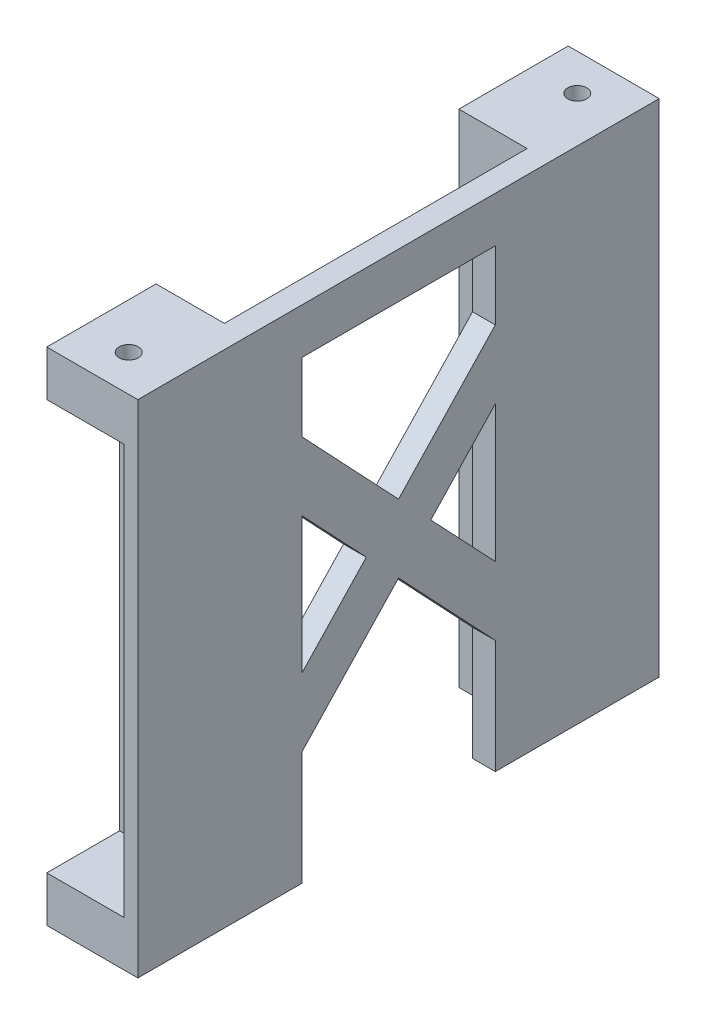
SolidWorks part; units mm, degrees
ref_plane "Спереди" through (0, 0, 0) normal (0, 0, 1) x (1, 0, 0)
ref_plane "Сверху" through (0, 0, 0) normal (0, 1, 0) x (1, 0, 0)
ref_plane "Справа" through (0, 0, 0) normal (1, 0, 0) x (0, 0, -1)
ref_plane "Плоскость4" through (0, 139.196, 0) normal (0, 1, 0) x (1, 0, 0)
sketch "Эскиз1" plane through (0, 139.196, 0) normal (0, 1, 0) x (1, 0, 0)
  line L9 (108.059, -32.2731) -> (128.059, -32.2731)
  line L10 (108.059, -32.2731) -> (128.059, -32.2731) construction
  line L11 (108.059, -32.2731) -> (108.059, -56.2731)
  line L14 (108.059, -56.2731) -> (123.059, -56.2731)
  line L15 (123.059, -56.2731) -> (123.059, -68.2731)
  line L16 (123.059, -68.2731) -> (128.059, -68.2731)
  line L17 (128.059, -34.1) -> (128.059, 34.1) construction
  line L18 (128.059, -68.2731) -> (128.059, -32.2731)
  circle A1 centre (120.059, -40.2731) radius 2.1
extrude "Бобышка-Вытянуть1" add sketch "Эскиз1" along normal blind 10
ref_plane "Плоскость5" through (0, 149.196, 0) normal (0, 1, 0) x (1, 0, 0)
sketch "Эскиз2" plane through (0, 149.196, 0) normal (0, 1, 0) x (1, 0, 0)
  line L9 (128.059, -32.2731) -> (125.059, -32.2731)
  line L10 (128.059, -32.2731) -> (108.059, -32.2731) construction
  line L11 (125.059, -32.2731) -> (125.059, -48.2731)
  line L12 (125.059, -48.2731) -> (108.059, -48.2731)
  line L13 (108.059, -48.2731) -> (21.559, -48.2731) construction
  line L14 (108.059, -32.2731) -> (108.059, -56.2731) construction
  line L15 (108.059, -48.2731) -> (108.059, -56.2731)
  line L16 (108.059, -56.2731) -> (123.059, -56.2731)
  line L17 (123.059, -56.2731) -> (123.059, -68.2731)
  line L18 (123.059, -68.2731) -> (128.059, -68.2731)
  line L19 (128.059, -68.2731) -> (128.059, -32.2731)
extrude "Бобышка-Вытянуть2" add sketch "Эскиз2" along normal blind 90
sketch "Эскиз3" plane through (0, 139.196, 0) normal (0, 1, 0) x (1, 0, 0)
  line L0 (123.059, -110.7731) -> (123.059, -122.7731)
  line L1 (123.059, -122.7731) -> (108.059, -122.7731)
  line L2 (108.059, -122.7731) -> (108.059, -146.7731)
  line L3 (108.059, -146.7731) -> (128.059, -146.7731)
  line L4 (128.059, -34.1) -> (128.059, 34.1) construction
  line L5 (128.059, -146.7731) -> (128.059, -110.7731)
  line L6 (128.059, -110.7731) -> (123.059, -110.7731)
  circle A0 centre (120.059, -138.7731) radius 2.1
extrude "Бобышка-Вытянуть3" add sketch "Эскиз3" along normal blind 10 separate body
sketch "Эскиз4" plane through (0, 149.196, 0) normal (0, 1, 0) x (1, 0, 0)
  line L0 (123.059, -110.7731) -> (123.059, -122.7731)
  line L1 (123.059, -122.7731) -> (108.059, -122.7731)
  line L2 (108.059, -122.7731) -> (108.059, -130.7731)
  line L3 (108.059, -130.7731) -> (125.059, -130.7731)
  line L4 (-8.25, -130.7731) -> (8.25, -130.7731) construction
  line L5 (125.059, -130.7731) -> (125.059, -146.7731)
  line L6 (108.059, -146.7731) -> (128.059, -146.7731) construction
  line L7 (125.059, -146.7731) -> (128.059, -146.7731)
  line L8 (128.059, -146.7731) -> (128.059, -110.7731)
  line L9 (128.059, -110.7731) -> (123.059, -110.7731)
extrude "Бобышка-Вытянуть4" add sketch "Эскиз4" along normal blind 90
ref_plane "Плоскость6" through (128.059, 0, 0) normal (1, 0, 0) x (0, 0, -1)
sketch "Эскиз5" plane through (128.059, 0, 0) normal (1, 0, 0) x (0, 0, -1)
  line L1 (-68.2731, 224.146) -> (-68.2731, 209.146)
  line L3 (-110.7731, 164.146) -> (-110.7731, 179.146)
  line L20 (-68.2731, 164.146) -> (-89.5231, 186.646)
  line L21 (-89.5231, 186.646) -> (-110.7731, 164.146)
  line L22 (-68.2731, 239.196) -> (-68.2731, 139.196) construction
  line L23 (-110.7731, 224.146) -> (-89.5231, 201.646)
  line L26 (-110.7731, 239.196) -> (-110.7731, 139.196) construction
  line L27 (-89.5231, 201.646) -> (-68.2731, 224.146)
  line L28 (-68.2731, 164.146) -> (-68.2731, 179.146)
  line L29 (-110.7731, 224.146) -> (-110.7731, 209.146)
  line L34 (-68.2731, 209.146) -> (-82.4398, 194.146)
  line L35 (-82.4398, 194.146) -> (-68.2731, 179.146)
  line L36 (-110.7731, 179.146) -> (-96.6065, 194.146)
  line L37 (-96.6065, 194.146) -> (-110.7731, 209.146)
extrude "Бобышка-Вытянуть5" add sketch "Эскиз5" against normal blind 5
ref_plane "Плоскость7" through (0, 239.196, 0) normal (0, 1, 0) x (1, 0, 0)
sketch "Эскиз6" plane through (0, 239.196, 0) normal (0, 1, 0) x (1, 0, 0)
  line L0 (108.059, -56.2731) -> (108.059, -32.2731)
  line L1 (108.059, -32.2731) -> (128.059, -32.2731)
  line L2 (128.059, -60.5) -> (128.059, 60.5) construction
  line L3 (108.059, -56.2731) -> (123.059, -56.2731)
  line L8 (108.059, -122.7731) -> (108.059, -146.7731)
  line L9 (108.059, -146.7731) -> (128.059, -146.7731)
  line L10 (108.059, -122.7731) -> (123.059, -122.7731)
  line L11 (123.059, -122.7731) -> (123.059, -56.2731)
  line L12 (128.059, -146.7731) -> (128.059, -32.2731)
  circle A4 centre (118.059, -40.2731) radius 2.1
  circle A5 centre (118.059, -138.7731) radius 2.1
extrude "Бобышка-Вытянуть6" add sketch "Эскиз6" along normal blind 10
